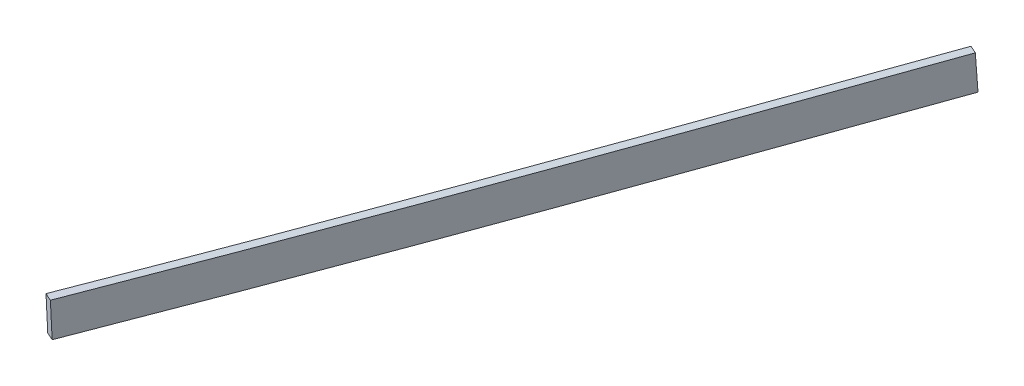
SolidWorks part; units mm, degrees
material "Balsa"
ref_plane "Front Plane" through (0, 0, 0) normal (0, 0, 1) x (1, 0, 0)
ref_plane "Top Plane" through (0, 0, 0) normal (0, 1, 0) x (1, 0, 0)
ref_plane "Right Plane" through (0, 0, 0) normal (1, 0, 0) x (0, 0, -1)
ref_plane "Plane1" through (190.506, 0, 85.0258) normal (-0.9132, 0, -0.4076) x (-0.4076, 0, 0.9132)
sketch "Sketch1" plane through (190.506, 0, 85.0258) normal (-0.9132, 0, -0.4076) x (-0.4076, 0, 0.9132)
  line L0 (-194.3863, 47.2218) -> (-194.0631, 53.5635) construction
  line L1 (-194.1618, 51.6279) -> (-194.6502, 38.9373)
  line L2 (-451.1919, 65.272) -> (-451.9312, 52.5936)
  spline S0 degree 3 poles (1812.2708, 99.2401) (1123.9274, 86.4332) (433.3974, 22.3312) (-275.0727, 55.1431) (-297.0958, 56.2628) (-341.1323, 58.6736) (-363.146, 59.9664) (-396.1631, 61.9582) (-407.1683, 62.6302) (-875.2034, 91.037) (-1332.6398, 111.9695) (-1868.4028, -1177.5019) knots -7.540663 -7.540663 -7.540663 -7.540663 0.25 0.25 0.5 0.5 0.75 0.75 0.875 0.875 6.065946 6.065946 6.065946 6.065946 only from (-186.9493, 51.3537) to (-451.1919, 65.272)
  spline S1 degree 3 poles (-194.1618, 51.6279) (-213.7927, 52.3835) (-233.4205, 53.214) (-275.0727, 55.1431) (-297.0958, 56.2628) (-341.1323, 58.6736) (-363.146, 59.9664) (-396.1631, 61.9582) (-407.1683, 62.6302) (-429.1792, 63.9662) (-440.1849, 64.6302) (-451.1919, 65.272) knots 0.027276 0.027276 0.027276 0.027276 0.25 0.25 0.5 0.5 0.75 0.75 0.875 0.875 1 1 1 1
  spline S2 degree 1 poles (-194.6502, 38.9373) (-451.9312, 52.5936) knots 0 0 1 1 construction
  spline S3 degree 3 poles (-194.6502, 38.9373) (-216.1202, 39.7637) (-259.0534, 41.5958) (-323.4277, 44.9052) (-377.0197, 48.0646) (-419.8518, 50.681) (-441.2344, 51.9698) (-451.9312, 52.5936) knots 0.027276 0.027276 0.027276 0.027276 0.270457 0.513638 0.756819 0.878409 1 1 1 1
  dimension "D1" = 12.7
extrude "Boss-Extrude1" add sketch "Sketch1" along normal blind 3.175
